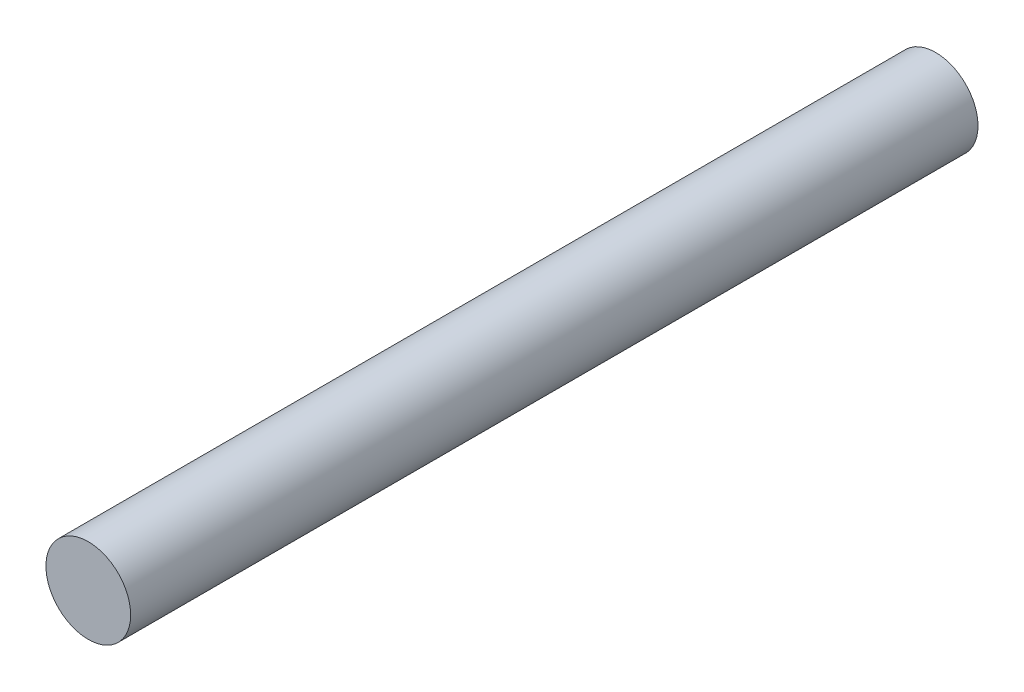
SolidWorks part; units mm, degrees
ref_plane "前视基准面" through (0, 0, 0) normal (0, 0, 1) x (1, 0, 0)
ref_plane "上视基准面" through (0, 0, 0) normal (0, 1, 0) x (1, 0, 0)
ref_plane "右视基准面" through (0, 0, 0) normal (1, 0, 0) x (0, 0, -1)
sketch "草图1" plane through (0, 0, 0) normal (0, 0, 1) x (1, 0, 0)
  circle A0 centre (0, 0) radius 1.5
  dimension "D1" = 3
extrude "凸台-拉伸1" add sketch "草图1" along normal blind 30
